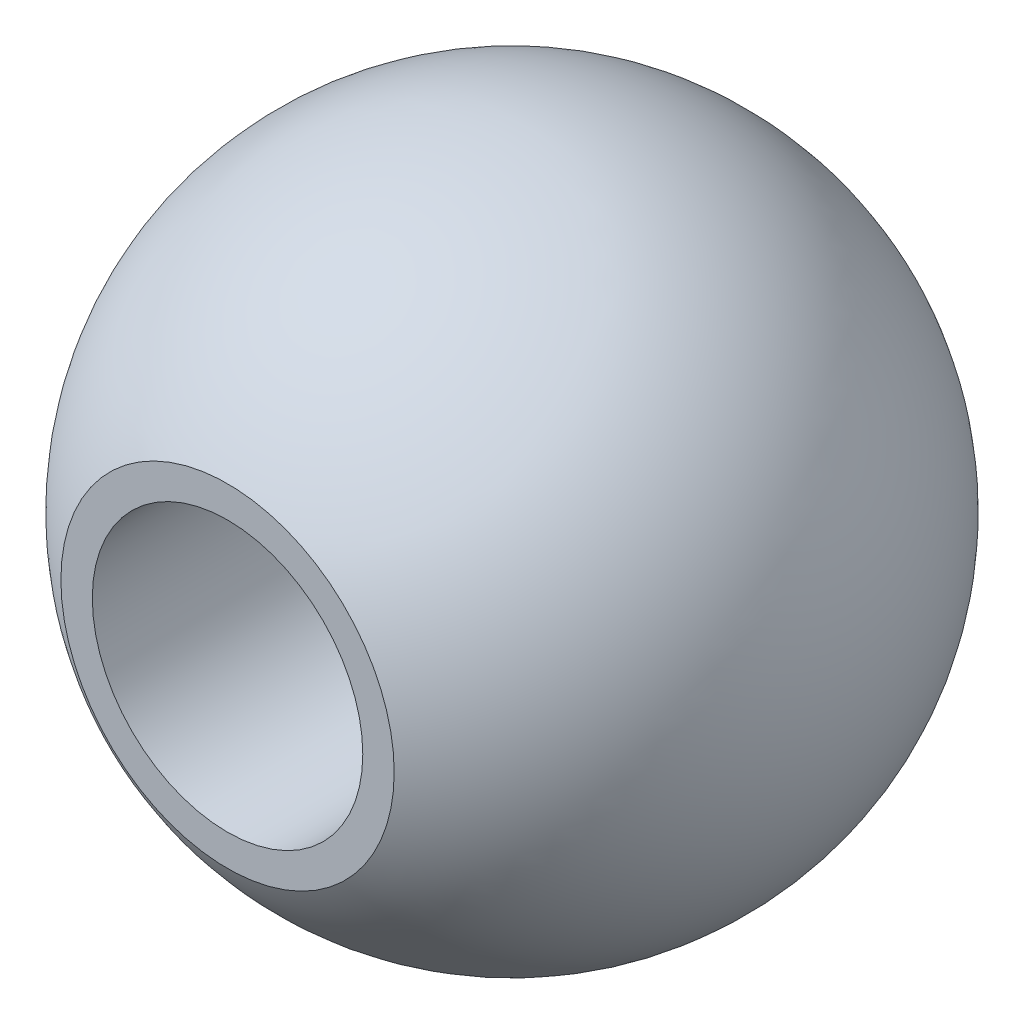
SolidWorks part; units mm, degrees
ref_plane "Front Plane" through (0, 0, 0) normal (0, 0, 1) x (1, 0, 0)
ref_plane "Top Plane" through (0, 0, 0) normal (0, 1, 0) x (1, 0, 0)
ref_plane "Right Plane" through (0, 0, 0) normal (1, 0, 0) x (0, 0, -1)
sketch "Sketch1" plane through (0, 0, 0) normal (0, 1, 0) x (1, 0, 0)
  line L0 (0, 3.365) -> (0, -3.365)
  line L1 (0, 3.365) -> (1.9715, 3.365)
  line L2 (0, 0) -> (3.9, 0) construction
  line L3 (0, -3.365) -> (1.9715, -3.365)
  arc A0 (1.9715, -3.365) -> (1.9715, 3.365) centre (0, 0) ccw
  dimension "D1" = 7.8
  dimension "D2" = 6.73
revolve "Revolve1" add sketch "Sketch1" angle 360 about L0
sketch "Sketch2" plane through (0, 0, 3.365) normal (0, 0, 1) x (1, 0, 0)
  circle A0 centre (0, 0) radius 1.6
  dimension "D1" = 3.2
extrude "Cut-Extrude1" cut sketch "Sketch2" against normal up to next
